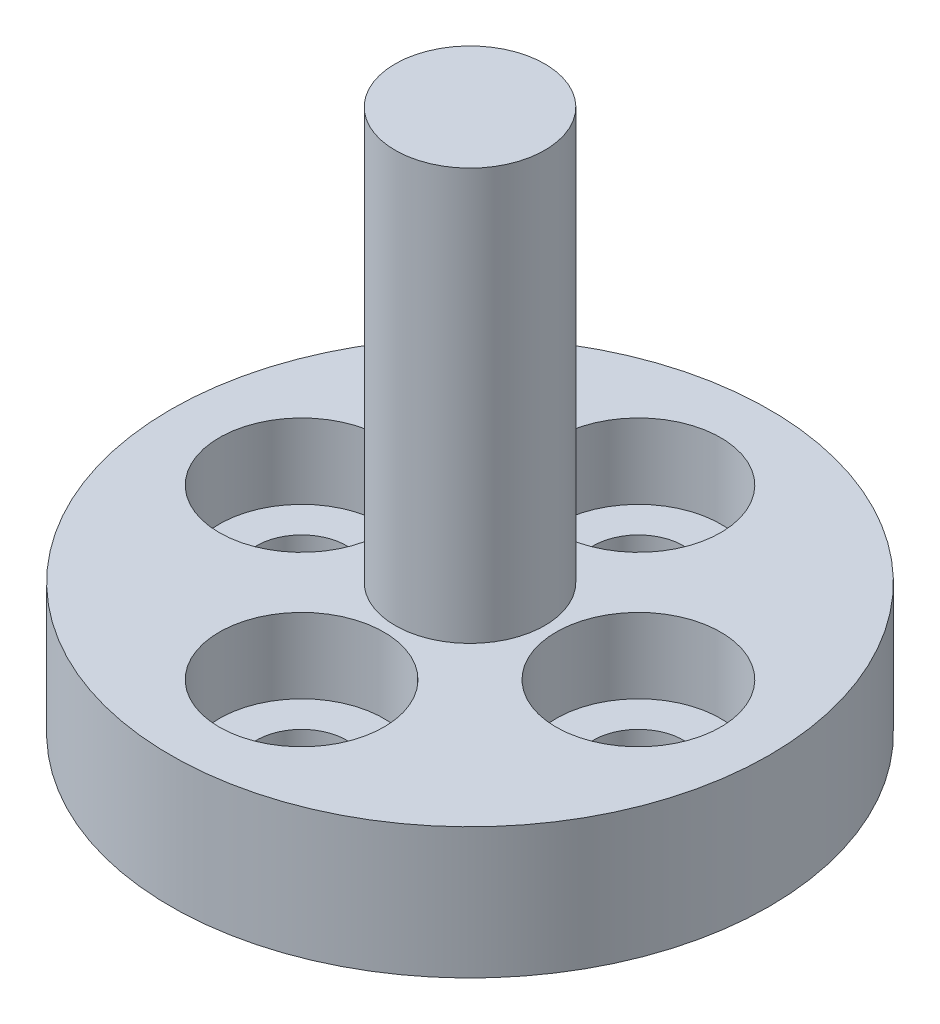
SolidWorks part; units mm, degrees
ref_plane "Front Plane" through (0, 0, 0) normal (0, 0, 1) x (1, 0, 0)
ref_plane "Top Plane" through (0, 0, 0) normal (0, 1, 0) x (1, 0, 0)
ref_plane "Right Plane" through (0, 0, 0) normal (1, 0, 0) x (0, 0, -1)
sketch "Sketch1" plane through (0, 0, 0) normal (0, 0, 1) x (1, 0, 0)
  line L0 (0, 0) -> (8, 0)
  line L1 (8, 0) -> (8, 3.5)
  line L2 (8, 3.5) -> (2, 3.5)
  line L3 (2, 3.5) -> (2, 14.5)
  line L4 (2, 14.5) -> (0, 14.5)
  line L5 (0, 14.5) -> (0, 0)
  dimension "D1" = 8
  dimension "D2" = 14.5
  dimension "D3" = 11
  dimension "D5" = 2
revolve "Revolve1" add sketch "Sketch1" angle 360 about L5
sketch "Sketch2" plane through (0, 3.5, 0) normal (0, 1, 0) x (1, 0, 0)
  circle A0 centre (0, 0) radius 4.5
  dimension "D1" = 9
hole_wizard "CBORE for M2 SHCS1" positions "Sketch3" profile "Sketch4" counterbore size "M2" standard "ANSI Metric" end condition through all
sketch "Sketch3" plane through (0, 3.5, 0) normal (0, 1, 0) x (1, 0, 0)
  circle A0 centre (0, 0) radius 4.5 construction
  point P0 (-4.5, 0)
  point P4 (0, 4.5)
  point P6 (4.5, 0)
  point P8 (0, -4.5)
sketch "Sketch4" plane through (-4.5, 3.5, 0) normal (1, 0, 0) x (0, 0, 1)
  line L0 (0, 0) -> (0, 3.5)
  line L1 (0, 3.5) -> (1.2, 3.5)
  line L3 (1.2, 3.5) -> (1.2, 2)
  line L4 (1.2, 2) -> (2.2, 2)
  line L5 (2.2, 2) -> (2.2, 0)
  line L7 (2.2, 0) -> (0, 0)
  line L11 (0, -6.35) -> (0, 107.95) construction
  dimension "Thru Hole Dia." = 2.4
  dimension "Thru Hole Depth" = 3.5
  dimension "C'Bore Dia." = 4.4
  dimension "C'Bore Depth" = 2
